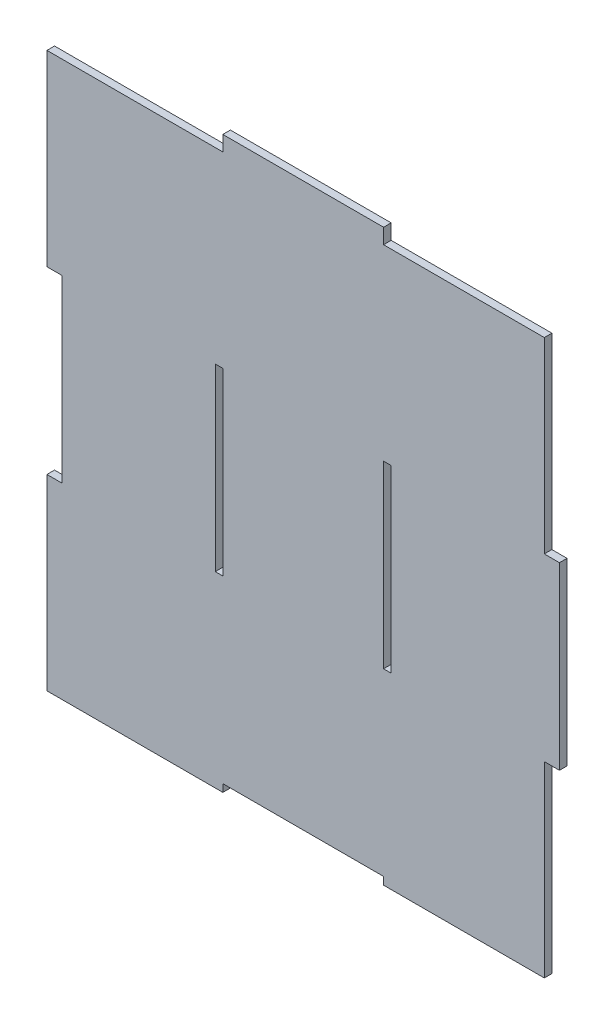
SolidWorks part; units mm, degrees
material "Delrin 2700 NC010, Low Viscosity Acetal Copolymer (SS)"
ref_plane "Front Plane" through (0, 0, 0) normal (0, 0, 1) x (1, 0, 0)
ref_plane "Top Plane" through (0, 0, 0) normal (0, 1, 0) x (1, 0, 0)
ref_plane "Right Plane" through (0, 0, 0) normal (1, 0, 0) x (0, 0, -1)
sketch "Sketch2" plane through (0, 0, 0) normal (0, 0, 1) x (1, 0, 0)
  line L0 (-113, 0) -> (-48.8417, 0)
  line L1 (-45.6667, 119.35) -> (-45.6667, 113)
  line L2 (-45.6667, 0) -> (21.6667, 0)
  line L3 (-45.6667, 119.35) -> (21.6667, 119.35)
  line L4 (95.35, 37.6667) -> (95.35, -37.6667)
  line L5 (-113, 37.6667) -> (-119.35, 37.6667)
  line L6 (-45.6667, 113) -> (21.6667, 113)
  line L7 (-12, 119.35) -> (-12, 113)
  line L8 (-113, 37.6667) -> (-113, -37.6667)
  line L9 (-113, 0) -> (-119.35, 0)
  line L10 (-45.6667, 116.175) -> (-116.175, 116.175)
  line L11 (-116.175, 116.175) -> (-116.175, 37.6667)
  line L12 (-116.175, 37.6667) -> (-113, 37.6667)
  line L13 (-113, 37.6667) -> (-113, -37.6667)
  line L14 (-48.8417, -37.6667) -> (-48.8417, 37.6667)
  line L15 (-48.8417, 37.6667) -> (-45.6667, 37.6667)
  line L16 (-45.6667, 37.6667) -> (-45.6667, -37.6667)
  line L17 (-119.35, 37.6667) -> (-119.35, -37.6667)
  line L18 (21.6667, 37.6667) -> (21.6667, -37.6667)
  line L19 (24.8417, 37.6667) -> (21.6667, 37.6667)
  line L20 (24.8417, -37.6667) -> (24.8417, 37.6667)
  line L21 (89, 37.6667) -> (89, -37.6667)
  line L22 (92.175, 37.6667) -> (89, 37.6667)
  line L23 (92.175, 116.175) -> (92.175, 37.6667)
  line L24 (-12, 119.35) -> (-12, -119.35)
  line L25 (21.6667, 116.175) -> (92.175, 116.175)
  line L26 (89, 0) -> (95.35, 0)
  line L27 (89, 37.6667) -> (89, -37.6667)
  line L28 (89, 37.6667) -> (95.35, 37.6667)
  line L29 (21.6667, 119.35) -> (21.6667, 113)
  line L30 (89, 0) -> (24.8417, 0)
  line L31 (21.6667, -119.35) -> (21.6667, -113)
  line L32 (89, -37.6667) -> (95.35, -37.6667)
  line L33 (21.6667, -116.175) -> (92.175, -116.175)
  line L34 (92.175, -116.175) -> (92.175, -37.6667)
  line L35 (92.175, -37.6667) -> (89, -37.6667)
  line L36 (24.8417, -37.6667) -> (21.6667, -37.6667)
  line L37 (-48.8417, -37.6667) -> (-45.6667, -37.6667)
  line L38 (-116.175, -37.6667) -> (-113, -37.6667)
  line L39 (-116.175, -116.175) -> (-116.175, -37.6667)
  line L40 (-45.6667, -116.175) -> (-116.175, -116.175)
  line L41 (-12, -119.35) -> (-12, -113)
  line L42 (-45.6667, -113) -> (21.6667, -113)
  line L43 (-113, -37.6667) -> (-119.35, -37.6667)
  line L44 (-45.6667, -119.35) -> (21.6667, -119.35)
  line L45 (-45.6667, -119.35) -> (-45.6667, -113)
  point P35 (-12, 0)
  point P36 (-12, 0)
  dimension "D1" = 3.175
  dimension "D2" = 37.6667
  dimension "D3" = 3.175
  dimension "D4" = 3.175
  dimension "D5" = 67.3333
  dimension "D6" = 67.3333
  dimension "D7" = 113
  dimension "D8" = 37.6667
  dimension "D9" = 101
  dimension "D10" = 3.175
  dimension "D11" = 3.175
  dimension "D13" = 0
  dimension "D14" = 0
extrude "Boss-Extrude1" add sketch "Sketch2" along normal blind 3.175 contours L24 L6 L1 L10 L11 L5 L8 L0 L14 L15 L16 L2 | L29 L3 L7 L6 | L30 L21 L22 L23 L25 L29 L6 L24 L2 L18 L19 L20 | L28 L22 L21 L26 L4 | L21 L32 L4 L26 | L24 L42 L31 L33 L34 L32 L21 L30 L20 L36 L18 L2 | L40 L45 L42 L24 L2 L16 L37 L14 L0 L8 L38 L39
sketch "Sketch3" plane through (0, 0, 3.175) normal (0, 0, 1) x (1, 0, 0)
  line L0 (-45.6667, -116.175) -> (-116.175, -116.175) construction
  line L1 (-116.175, 116.175) -> (-119.35, 116.175)
  line L2 (-116.175, 116.175) -> (-116.175, -116.175)
  line L3 (-116.175, -116.175) -> (-119.35, -116.175)
  line L4 (-119.35, 116.175) -> (-119.35, -116.175)
  line L5 (-116.175, -37.6667) -> (-113, -37.6667) construction
  line L6 (-113, 37.6667) -> (-119.35, 37.6667)
  line L7 (-113, 37.6667) -> (-113, -37.6667)
  line L8 (-113, -37.6667) -> (-119.35, -37.6667)
  line L9 (-119.35, 37.6667) -> (-119.35, -37.6667)
  line L10 (-45.6667, 119.35) -> (21.6667, 119.35) construction
  line L11 (21.6667, 116.175) -> (-45.6667, 116.175)
  line L12 (21.6667, 116.175) -> (21.6667, 122.525)
  line L13 (21.6667, 122.525) -> (-45.6667, 122.525)
  line L14 (-45.6667, 116.175) -> (-45.6667, 122.525)
  line L15 (-45.6667, 119.35) -> (-45.6667, 116.175) construction
  line M5 (21.6667, 119.35) -> (-45.6667, 119.35)
  line M8 (-116.175, 116.175) -> (-116.175, 37.6667)
  line M12 (-116.175, -37.6667) -> (-116.175, -116.175)
  dimension "D1" = 3.175
  dimension "D2" = 0
  dimension "D3" = 0
  dimension "D4" = 3.175
  dimension "D5" = 0
extrude "Boss-Extrude2" add sketch "Sketch3" against normal blind 3.175 contours L6 L1 L4 M8 | L8 L4 L3 M12 | L14 L12 L13 M5
sketch "Sketch4" plane through (0, 0, 3.175) normal (0, 0, 1) x (1, 0, 0)
  line L0 (21.6667, 116.175) -> (92.175, 116.175) construction
  line L1 (95.35, 37.6667) -> (89, 37.6667)
  line L2 (95.35, 37.6667) -> (95.35, 116.175)
  line L3 (95.35, 116.175) -> (89, 116.175)
  line L4 (89, 37.6667) -> (89, 116.175)
  line L5 (21.6667, -116.175) -> (92.175, -116.175) construction
  line L6 (89, 37.6667) -> (95.35, 37.6667)
  line L7 (89, 37.6667) -> (89, -37.6667)
  line L8 (89, -37.6667) -> (95.35, -37.6667)
  line L9 (95.35, 37.6667) -> (95.35, -37.6667)
  line L10 (95.35, -37.6667) -> (89, -37.6667)
  line L11 (95.35, -37.6667) -> (95.35, -116.175)
  line L12 (95.35, -116.175) -> (89, -116.175)
  line L13 (89, -37.6667) -> (89, -116.175)
  line L14 (92.175, 116.175) -> (92.175, 37.6667) construction
  line L16 (92.175, 116.175) -> (89, 116.175)
  line L17 (92.175, 116.175) -> (92.175, -116.175)
  line L18 (92.175, -116.175) -> (89, -116.175)
  line L19 (89, 116.175) -> (89, -116.175)
  line M13 (21.6667, -116.175) -> (92.175, -116.175)
  line M14 (92.175, -116.175) -> (92.175, -37.6667)
  line M18 (92.175, 37.6667) -> (92.175, 116.175)
  line M19 (92.175, 116.175) -> (21.6667, 116.175)
  dimension "D1" = 3.175
extrude "Cut-Extrude1" cut sketch "Sketch4" against normal blind 3.175 contours L4 L1 M18 M19 | L8 L13 M13 M14
equation "\"D8@Sketch2\"=\"D2@Sketch2\""
equation "\"D11@Sketch2\"=\"D3@Sketch2\""
equation "\"D4@Sketch2\"=\"D3@Sketch2\""
equation "\"D10@Sketch2\"=\"D3@Sketch2\""
equation "\"Resolution Projector X\"= 1920'a_ resolution data"
equation "\"Resolution Projector Y\"= 1080'a_ resolution data"
equation "\"Resolution Build\"= 0.1'a_ resolution data"
equation "\"Size Build Volume X\"= \"Resolution Projector X\" * \"Resolution Build\"'b_ build volume data"
equation "\"Size Build Volume Y\"= 2 * \"Resolution Projector Y\" * \"Resolution Build\"'b_ build volume data"
equation "\"Size Build Volume Z\"= \"Size Build Volume Y\"'b_ build volume data"
equation "\"Size Enclosure Internal X\"= 350mm'c_ size enclosure Internal data"
equation "\"Size Enclosure Internal Y\"= \"Size Enclosure Internal X\"'c_ size enclosure Internal data"
equation "\"Size Enclosure Internal Z\"= \"Size Enclosure Internal X\"'c_ size enclosure Internal data"
equation "\"Size Enclosure External Z\"= 1000mm'c_ size enclosure External data"
equation "\"Clearance Vat\"= 10mm'd_ clearance vat data"
equation "\"Size Vat X\"= \"Size Build Volume X\" + \"Clearance Vat\"'f_ size vat data"
equation "\"Size Vat Y\"= \"Size Build Volume Y\" + \"Clearance Vat\"'f_ size vat data"
equation "\"Size Vat Z\"= \"Size Build Volume Z\" + \"Clearance Vat\"'f_ size vat data"
equation "\"Thickness Vat\"= 3.175mm'g_ thickness vat data"
equation "\"width rib\"= 2 * \"Thickness Vat\"'g_ thickness of the Rib"
equation "\"width Lip on rib\"= \"Thickness Vat\" * 2'g_ thickness of the lip connected to the tab"
equation "\"height Lip on rib\" = \"width Lip on rib\"'g_ height of lip on rib structure"
equation "\"height adjustment\" = \"Thickness Vat\" * 2'g_ height adjustment for lip.  This flushes the top part of the tab to top of the walls"
equation "\"goofy tab x\"= \"Size Vat X\" * ( 1 / 3 ) - \"width rib\"'h_ goofy slot found on rib X"
equation "\"goofy tab y\"= \"Size Vat Y\" * ( 1 / 3 ) - \"width rib\"'h_ goofy slot found on rib Y"
equation "\"D9@Sketch2\"=\"Size Vat X\"/2mm"
equation "\"D5@Sketch2\"=\"D6@Sketch2\""
equation "\"D1@Sketch2\"=\"D10@Sketch2\""
equation "\"D2@Sketch2\"=\"D7@Sketch2\"/3"
equation "\"D6@Sketch2\"=\"Size Vat X\"/3"
equation "\"D3@Sketch2\"=\"Thickness Vat\""
equation "\"D7@Sketch2\"=\"Size Vat Z\"/2"
equation "\"D1@Boss-Extrude1\"=\"Thickness Vat\""
equation "\"D1@Sketch3\"=\"Thickness Vat\""
equation "\"D1@Boss-Extrude2\"=\"Thickness Vat\""
equation "\"D1@Sketch4\"=\"Thickness Vat\""
equation "\"D1@Cut-Extrude1\"=\"Thickness Vat\""
equation "\"D4@Sketch3\"=\"Thickness Vat\""
